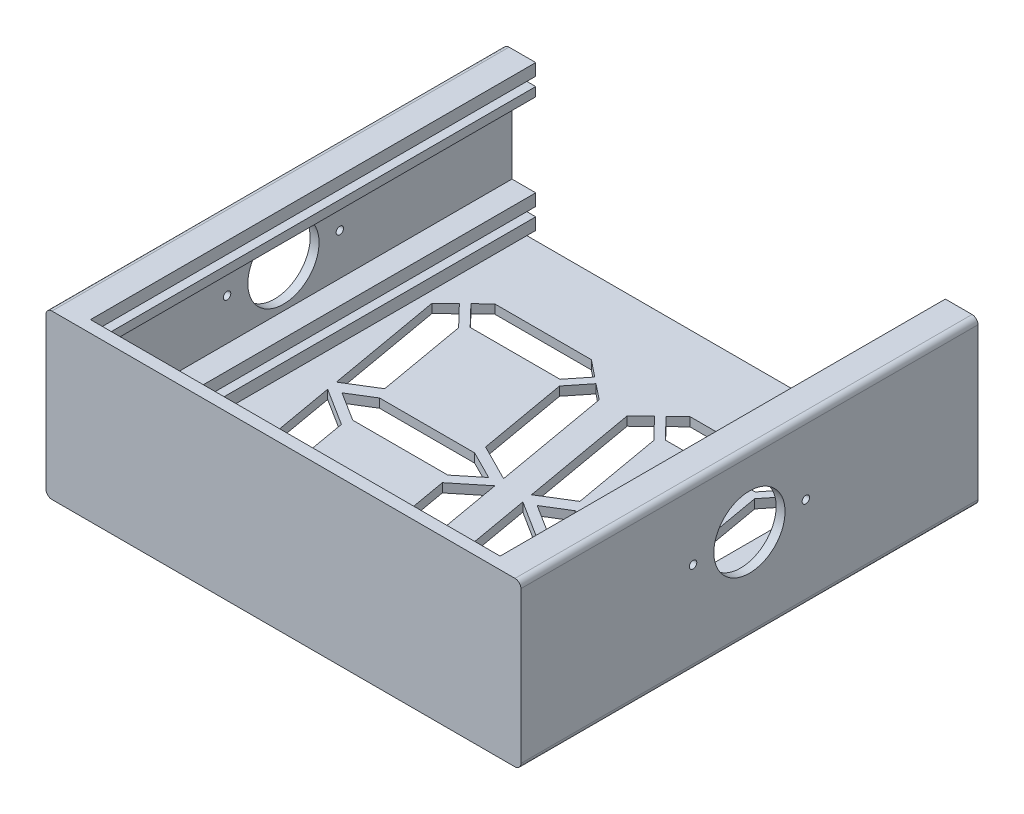
SolidWorks part; units mm, degrees
ref_plane "Alzado" through (0, 0, 0) normal (0, 0, 1) x (1, 0, 0)
ref_plane "Planta" through (0, 0, 0) normal (0, 1, 0) x (1, 0, 0)
ref_plane "Vista lateral" through (0, 0, 0) normal (1, 0, 0) x (0, 0, -1)
sketch "Sketch3" plane through (0, 0, 0) normal (0, 0, 1) x (1, 0, 0)
  line L0 (-80, 0) -> (80, 0)
  line L1 (-80, 0) -> (-80, 10)
  line L2 (-80, 10) -> (-69, 10)
  line L3 (-69, 10) -> (-69, 6)
  line L4 (-69, 6) -> (-77, 6)
  line L5 (-77, 6) -> (-77, 3)
  line L6 (-77, 3) -> (77, 3)
  line L8 (0, -2.3975) -> (0, 0) construction
  line L9 (77, 6) -> (77, 3)
  line L10 (69, 6) -> (77, 6)
  line L11 (69, 10) -> (69, 6)
  line L12 (80, 10) -> (69, 10)
  line L13 (80, 0) -> (80, 10)
  line L14 (0, 3) -> (0, 3.4015) construction
  point P4 (0, 0)
  dimension "D1" = 154
  dimension "D2" = 3
  dimension "D3" = 3
  dimension "D4" = 3
  dimension "D5" = 4
  dimension "D6" = 8
extrude "Boss-Extrude4" add sketch "Sketch3" along normal blind 154 contours L0 L13 L12 L11 L10 L9 L6 L5 L4 L3 L2 L1
sketch "Sketch11" plane through (-69, 0, 0) normal (1, 0, 0) x (0, 0, -1)
  line L1 (-154, 10) -> (-150, 10)
  line L2 (-154, 10) -> (-154, 3)
  line L3 (-154, 3) -> (-150, 3)
  line L4 (-150, 10) -> (-150, 3)
  point P5 (-150, 6.5)
  dimension "D1" = 4
extrude "Boss-Extrude5" add sketch "Sketch11" along normal through all and the other way up to next
sketch "Sketch13" plane through (0, 10, 0) normal (0, 1, 0) x (1, 0, 0)
  line L0 (80, 0) -> (77, 0)
  line L1 (77, 0) -> (77, -150)
  line L2 (77, -150) -> (-77, -150)
  line L3 (-77, -150) -> (-77, 0)
  line L4 (-77, 0) -> (-80, 0)
  line L5 (-80, 0) -> (-80, -154)
  line L6 (-80, -154) -> (80, -154)
  line L7 (80, -154) -> (80, 0)
  line L8 (77, -150) -> (77, 0) construction
  line L9 (80, 0) -> (69, 0) construction
  line L10 (-80, 0) -> (-69, 0) construction
  line L11 (69, -150) -> (-69, -150) construction
extrude "Boss-Extrude6" add sketch "Sketch13" along normal blind 45
sketch "Sketch15" plane through (0, 0, 150) normal (0, 0, -1) x (-1, 0, 0)
  line L0 (-69, 6) -> (-77, 6) construction
  line L1 (69, 6) -> (-69, 6)
  line L2 (69, 6) -> (69, 10)
  line L3 (69, 10) -> (-69, 10)
  line L4 (-69, 6) -> (-69, 10)
  line L5 (-77, 10) -> (-77, 55) construction
  line L7 (69, 10) -> (69, 6) construction
  line L8 (77, 13) -> (-77, 13)
  line L9 (77, 13) -> (77, 17)
  line L10 (77, 17) -> (-77, 17)
  line L11 (-77, 13) -> (-77, 17)
  line L18 (77, 55) -> (77, 10) construction
  dimension "D1" = 3
  dimension "D3" = 4
extrude "Boss-Extrude7" add sketch "Sketch15" along normal blind 8
sketch "Sketch16" plane through (-77, 0, 0) normal (1, 0, 0) x (0, 0, -1)
  line L0 (0, 10) -> (0, 6) construction
  line L1 (-142, 13) -> (-142, 17) construction
  line L2 (0, 55) -> (0, 10) construction
  line L3 (-142, 17) -> (-150, 17) construction
  line L5 (-150, 45) -> (0, 45)
  line L6 (-142, 17) -> (0, 17)
  line L7 (-142, 17) -> (-142, 13)
  line L8 (-142, 13) -> (0, 13)
  line L9 (0, 17) -> (0, 13)
  line L10 (-150, 48) -> (0, 48)
  line L11 (0, 48) -> (0, 45)
  line L12 (-150, 55) -> (-150, 51)
  line L14 (-150, 51) -> (0, 51)
  line L15 (0, 51) -> (0, 55)
  line L16 (0, 55) -> (-150, 55)
  line L17 (-150, 48) -> (-150, 45)
  line L19 (-150, 55) -> (0, 55) construction
  line L20 (-150, 55) -> (-150, 17) construction
  dimension "D1" = 4
  dimension "D2" = 3
  dimension "D3" = 3
  dimension "D4" = 3
extrude "Boss-Extrude8" add sketch "Sketch16" along normal blind 8
mirror "Mirror1" about plane through (0, 0, 0) normal (1, 0, 0) of "Boss-Extrude8"
sketch "Sketch19" plane through (80, 0, 0) normal (1, 0, 0) x (0, 0, -1)
  line L0 (-77, 55) -> (-77, 0) construction
  line L4 (-89, 31) -> (-65, 31) construction
  line L9 (-154, 55) -> (0, 55) construction
  line L10 (-154, 0) -> (0, 0) construction
  circle A0 centre (-77, 31) radius 12
  circle A1 centre (-58, 31) radius 1.25
  circle A2 centre (-96, 31) radius 1.25
  dimension "D1" = 24
  dimension "D2" = 24
  dimension "D3" = 2.5
  dimension "D4" = 7
extrude "Cut-Extrude2" cut sketch "Sketch19" against normal through all both and the other way through all
sketch "Sketch23" plane through (0, 0, 0) normal (0, -1, 0) x (1, 0, 0)
  line L0 (-121.4869, 35.4036) -> (-91.4869, 35.4036)
  line L1 (-91.4869, 35.4036) -> (-84.2782, 40.4629)
  line L2 (-84.2782, 40.4629) -> (-87.7457, 45.4036)
  line L3 (-87.7457, 45.4036) -> (-119.7237, 45.4036)
  line L4 (-119.7237, 45.4036) -> (-125.6072, 41.2743)
  line L5 (-125.6072, 41.2743) -> (-121.4869, 35.4036)
  line L6 (-86.9751, 47.7728) -> (-82.1493, 75.1414)
  line L7 (-82.1493, 75.1414) -> (-75.8378, 80.2286)
  line L8 (-75.8378, 80.2286) -> (-71.9488, 75.4036)
  line L9 (-86.9751, 47.7728) -> (-82.6478, 41.6072)
  line L10 (-82.6478, 41.6072) -> (-77.2386, 45.4036)
  line L11 (-77.2386, 45.4036) -> (-71.9488, 75.4036)
  line L12 (-75.5209, 82.0262) -> (-70.2605, 84.9783)
  line L13 (-70.2605, 84.9783) -> (-64.0537, 120.1793)
  line L14 (-64.0537, 120.1793) -> (-67.9896, 124.7385)
  line L15 (-67.9896, 124.7385) -> (-74.3762, 119.2249)
  line L16 (-74.3762, 119.2249) -> (-79.666, 89.2249)
  line L17 (-79.666, 89.2249) -> (-75.5209, 82.0262)
  line L18 (-82.6478, 41.6072) -> (-67.9896, 124.7385) construction
  line L19 (-111.1826, 124.7385) -> (-67.9896, 124.7385) construction
  line L20 (-107.2467, 120.1793) -> (-64.0537, 120.1793) construction
  line L21 (-117.5692, 119.2249) -> (-74.3762, 119.2249) construction
  line L22 (-118.7139, 82.0262) -> (-75.5209, 82.0262) construction
  line L23 (-113.4536, 84.9783) -> (-70.2605, 84.9783) construction
  line L24 (-122.859, 89.2249) -> (-79.666, 89.2249) construction
  line L25 (-115.1419, 75.4036) -> (-71.9488, 75.4036) construction
  line L26 (-125.3423, 75.1414) -> (-82.1493, 75.1414) construction
  line L27 (-120.4317, 45.4036) -> (-77.2386, 45.4036) construction
  line L28 (-130.1682, 47.7728) -> (-86.9751, 47.7728) construction
  line L29 (-125.8409, 41.6072) -> (-82.6478, 41.6072) construction
  line L30 (-105.3849, 120.2859) -> (-74.5419, 120.2859)
  line L31 (-74.5419, 120.2859) -> (-68.5852, 125.4284)
  line L32 (-68.5852, 125.4284) -> (-72.7787, 130.2859)
  line L33 (-72.7787, 130.2859) -> (-104.7566, 130.2859)
  line L34 (-104.7566, 130.2859) -> (-110.0631, 125.7049)
  line L35 (-110.0631, 125.7049) -> (-105.3849, 120.2859)
  line L36 (-119.0309, 80.2286) -> (-75.8378, 80.2286) construction
  line L38 (-130.1682, 47.7728) -> (-125.3423, 75.1414)
  line L39 (-125.3423, 75.1414) -> (-119.0309, 80.2286)
  line L40 (-119.0309, 80.2286) -> (-115.1419, 75.4036)
  line L41 (-130.1682, 47.7728) -> (-125.8409, 41.6072)
  line L42 (-125.8409, 41.6072) -> (-120.4317, 45.4036)
  line L43 (-120.4317, 45.4036) -> (-115.1419, 75.4036)
  line L44 (-118.7139, 82.0262) -> (-113.4536, 84.9783)
  line L45 (-113.4536, 84.9783) -> (-107.2467, 120.1793)
  line L46 (-107.2467, 120.1793) -> (-111.1826, 124.7385)
  line L47 (-111.1826, 124.7385) -> (-117.5692, 119.2249)
  line L48 (-117.5692, 119.2249) -> (-122.859, 89.2249)
  line L49 (-122.859, 89.2249) -> (-118.7139, 82.0262)
  line L50 (-125.8409, 41.6072) -> (-111.1826, 124.7385) construction
  line L55 (-87.7457, 45.4036) -> (-72.7787, 130.2859)
  line L56 (-121.4869, 35.4036) -> (-104.7566, 130.2859) construction
  dimension "D1" = 80
  dimension "D2" = 52.5368
  dimension "D4" = 30
  dimension "D5" = 30
sketch "Version 1" plane through (0, 0, 0) normal (0, -1, 0) x (1, 0, 0)
  line L0 (17.6283, 7.3254) -> (47.1035, 7.3254)
  line L1 (47.1035, 7.3254) -> (51.1504, 11.3591)
  line L2 (51.1504, 11.3591) -> (46.7616, 17.3254)
  line L3 (46.7616, 17.3254) -> (18.8884, 17.3254)
  line L4 (18.8884, 17.3254) -> (13.6565, 11.1604)
  line L5 (13.6565, 11.1604) -> (17.6283, 7.3254)
  line L6 (18.5241, 19.3035) -> (12.5336, 12.2447)
  line L7 (23.3426, 46.6307) -> (54.2531, 46.6307) construction
  line L8 (14.1831, 52.2722) -> (23.3426, 46.6307)
  line L9 (23.3426, 46.6307) -> (18.5241, 19.3035)
  line L10 (12.5336, 12.2447) -> (7.912, 16.7071)
  line L11 (7.912, 16.7071) -> (14.1831, 52.2722)
  line L12 (49.2177, 18.0734) -> (52.8849, 13.088)
  line L13 (52.8849, 13.088) -> (59.6887, 19.8696)
  line L14 (59.6887, 19.8696) -> (65.4021, 52.2722)
  line L15 (14.1831, 52.2722) -> (65.4021, 52.2722) construction
  line L16 (65.4021, 52.2722) -> (54.2531, 46.6307)
  line L17 (54.2531, 46.6307) -> (49.2177, 18.0734)
  line L18 (18.2172, 54.0616) -> (24.941, 49.9203)
  line L19 (24.941, 49.9203) -> (54.0632, 49.9203)
  line L20 (54.0632, 49.9203) -> (62.2475, 54.0616)
  line L21 (62.2475, 54.0616) -> (55.9407, 59.9203)
  line L22 (55.9407, 59.9203) -> (26.7795, 59.9203)
  line L23 (26.7795, 59.9203) -> (18.2172, 54.0616)
  line L24 (14.7578, 55.5316) -> (20.5772, 88.5347)
  line L25 (20.5772, 88.5347) -> (25.4267, 92.8942)
  line L26 (25.4267, 92.8942) -> (30.5042, 87.246)
  line L27 (30.5042, 87.246) -> (26.3053, 63.4328)
  line L28 (26.3053, 63.4328) -> (14.7578, 55.5316)
  line L29 (57.2158, 63.4328) -> (65.9409, 55.3277)
  line L30 (65.9409, 55.3277) -> (71.7962, 88.5347)
  line L31 (71.7962, 88.5347) -> (67.1519, 93.2534)
  line L32 (67.1519, 93.2534) -> (61.4147, 87.246)
  line L33 (61.4147, 87.246) -> (57.2158, 63.4328)
  line L34 (26.3053, 63.4328) -> (57.2158, 63.4328) construction
  line L35 (18.2172, 54.0616) -> (62.2475, 54.0616) construction
  line L36 (26.9247, 94.2408) -> (31.2033, 89.4813)
  line L37 (31.2033, 89.4813) -> (60.7361, 89.4813)
  line L38 (60.7361, 89.4813) -> (65.724, 94.7042)
  line L39 (65.724, 94.7042) -> (61.0223, 99.4813)
  line L40 (61.0223, 99.4813) -> (32.7542, 99.4813)
  line L41 (32.7542, 99.4813) -> (26.9247, 94.2408)
  line L42 (20.5772, 88.5347) -> (71.7962, 88.5347) construction
  line L43 (30.5042, 87.246) -> (61.4147, 87.246) construction
  dimension "D1" = 80
  dimension "D2" = 37.4939
  dimension "D3" = 40.0275
  dimension "D4" = 44.0303
  dimension "D5" = 27.3271
sketch "Sketch27" plane through (0, 0, 0) normal (0, -1, 0) x (1, 0, 0)
  line L0 (-80, 0) -> (80, 0) construction
  line L1 (2.5, 154) -> (2.5, 0) construction
  line L2 (-68.253, 35.7252) -> (-80, 35.7252) construction
  line L3 (-2.5, 154) -> (-2.5, 0) construction
  line L48 (-80, 154) -> (-80, 0) construction
  line L49 (0, 77) -> (-80, 77) construction
  line L51 (0, 0) -> (0, 154) construction
  line L52 (-80, 154) -> (80, 154) construction
  line B0 (-57.4785, 25.3217) -> (-24.9357, 25.3217)
  line B1 (-24.9357, 25.3217) -> (-19.3054, 29.8193)
  line B2 (-19.3054, 29.8193) -> (-24.4996, 36.3217)
  line B3 (-24.4996, 36.3217) -> (-54.7714, 36.3217)
  line B4 (-54.7714, 36.3217) -> (-61.5742, 29.2763)
  line B5 (-61.5742, 29.2763) -> (-57.4785, 25.3217)
  line B6 (-56.6171, 38.3693) -> (-63.5525, 31.1865)
  line B7 (-51.2841, 68.6138) -> (-17.2826, 68.6138) construction
  line B8 (-61.3596, 74.8195) -> (-51.2841, 68.6138)
  line B9 (-51.2841, 68.6138) -> (-56.6171, 38.3693)
  line B10 (-63.5525, 31.1865) -> (-68.253, 35.7252)
  line B11 (-68.253, 35.7252) -> (-61.3596, 74.8195)
  line B12 (-22.6155, 38.3693) -> (-17.1568, 31.5357)
  line B13 (-17.1568, 31.5357) -> (-11.9121, 35.7252)
  line B14 (-11.9121, 35.7252) -> (-5.0187, 74.8195)
  line B15 (-61.3596, 74.8195) -> (-5.0187, 74.8195) construction
  line B16 (-5.0187, 74.8195) -> (-17.2826, 68.6138)
  line B17 (-17.2826, 68.6138) -> (-22.6155, 38.3693)
  line B18 (-57.2666, 77) -> (-49.4345, 72.1761)
  line B19 (-49.4345, 72.1761) -> (-17.4001, 72.1761)
  line B20 (-17.4001, 72.1761) -> (-7.8667, 77)
  line B21 (-7.8667, 77) -> (-15.4605, 83.1761)
  line B22 (-15.4605, 83.1761) -> (-47.4949, 83.1761)
  line B23 (-47.4949, 83.1761) -> (-57.2666, 77)
  line B24 (-60.7343, 78.3659) -> (-53.8409, 117.4601)
  line B25 (-53.8409, 117.4601) -> (-47.5815, 123.0871)
  line B26 (-47.5815, 123.0871) -> (-42.6469, 117.5979)
  line B27 (-42.6469, 117.5979) -> (-48.1637, 86.3109)
  line B28 (-48.1637, 86.3109) -> (-60.7343, 78.3659)
  line B29 (-14.1621, 86.3109) -> (-4.3934, 78.3659)
  line B30 (-4.3934, 78.3659) -> (2.5, 117.4601)
  line B31 (2.5, 117.4601) -> (-2.2352, 123.0388)
  line B32 (-2.2352, 123.0388) -> (-8.6454, 117.5979)
  line B33 (-8.6454, 117.5979) -> (-14.1621, 86.3109)
  line B34 (-48.1637, 86.3109) -> (-14.1621, 86.3109) construction
  line B35 (-57.2666, 77) -> (-7.8667, 77) construction
  line B36 (-45.5364, 124.9256) -> (-41.4445, 120.3738)
  line B37 (-41.4445, 120.3738) -> (-9.6247, 120.3738)
  line B38 (-9.6247, 120.3738) -> (-4.0148, 125.1354)
  line B39 (-4.0148, 125.1354) -> (-9.3098, 131.3738)
  line B40 (-9.3098, 131.3738) -> (-38.3635, 131.3738)
  line B41 (-38.3635, 131.3738) -> (-45.5364, 124.9256)
  line B42 (-53.8409, 117.4601) -> (2.5, 117.4601) construction
  line B43 (-42.6469, 117.5979) -> (-8.6454, 117.5979) construction
  line B44 (-56.6171, 38.3693) -> (-22.6155, 38.3693) construction
  line B45 (-68.253, 35.7252) -> (-11.9121, 35.7252) construction
  line B46 (-49.4345, 72.1761) -> (-47.4949, 83.1761) construction
  line B47 (-17.4001, 72.1761) -> (-15.4605, 83.1761) construction
  line B48 (-63.5525, 31.1865) -> (-61.5742, 29.2763) construction
  line B49 (-19.3054, 29.8193) -> (-17.1568, 31.5357) construction
  line B50 (-47.5815, 123.0871) -> (-45.5364, 124.9256) construction
  line B51 (-4.0148, 125.1354) -> (-2.2352, 123.0388) construction
  line B52 (8.2745, 25.3217) -> (40.8173, 25.3217)
  line B53 (40.8173, 25.3217) -> (46.4476, 29.8193)
  line B54 (46.4476, 29.8193) -> (41.2534, 36.3217)
  line B55 (41.2534, 36.3217) -> (10.9816, 36.3217)
  line B56 (10.9816, 36.3217) -> (4.1788, 29.2763)
  line B57 (4.1788, 29.2763) -> (8.2745, 25.3217)
  line B58 (9.1359, 38.3693) -> (2.2005, 31.1865)
  line B59 (4.3934, 74.8195) -> (14.4688, 68.6138)
  line B60 (14.4688, 68.6138) -> (9.1359, 38.3693)
  line B61 (2.2005, 31.1865) -> (-2.5, 35.7252)
  line B62 (-2.5, 35.7252) -> (4.3934, 74.8195)
  line B63 (43.1374, 38.3693) -> (48.5962, 31.5357)
  line B64 (48.5962, 31.5357) -> (53.8409, 35.7252)
  line B65 (53.8409, 35.7252) -> (60.7343, 74.8195)
  line B66 (60.7343, 74.8195) -> (48.4704, 68.6138)
  line B67 (48.4704, 68.6138) -> (43.1374, 38.3693)
  line B68 (8.4863, 77) -> (16.3185, 72.1761)
  line B69 (16.3185, 72.1761) -> (48.3529, 72.1761)
  line B70 (48.3529, 72.1761) -> (57.8862, 77)
  line B71 (57.8862, 77) -> (50.2925, 83.1761)
  line B72 (50.2925, 83.1761) -> (18.2581, 83.1761)
  line B73 (18.2581, 83.1761) -> (8.4863, 77)
  line B74 (5.0187, 78.3659) -> (11.9121, 117.4601)
  line B75 (11.9121, 117.4601) -> (18.1715, 123.0871)
  line B76 (18.1715, 123.0871) -> (23.1061, 117.5979)
  line B77 (23.1061, 117.5979) -> (17.5893, 86.3109)
  line B78 (17.5893, 86.3109) -> (5.0187, 78.3659)
  line B79 (51.5908, 86.3109) -> (61.3596, 78.3659)
  line B80 (61.3596, 78.3659) -> (68.253, 117.4601)
  line B81 (68.253, 117.4601) -> (63.5178, 123.0388)
  line B82 (63.5178, 123.0388) -> (57.1076, 117.5979)
  line B83 (57.1076, 117.5979) -> (51.5908, 86.3109)
  line B84 (8.4863, 77) -> (57.8862, 77) construction
  line B85 (20.2166, 124.9256) -> (24.3085, 120.3738)
  line B86 (24.3085, 120.3738) -> (56.1283, 120.3738)
  line B87 (56.1283, 120.3738) -> (61.7382, 125.1354)
  line B88 (61.7382, 125.1354) -> (56.4432, 131.3738)
  line B89 (56.4432, 131.3738) -> (27.3895, 131.3738)
  line B90 (27.3895, 131.3738) -> (20.2166, 124.9256)
  dimension "D1" = 2.5
  dimension "D2" = 2.5
sketch_block_instance "Block1-1"
sketch_block "Block1" parameters "D1"=80, "D2"=44.909, "D3"=1.6361, "D4"=28.8815, "D5"=29.5328, "D6"=28.4427, "D7"=29.1222, "D8"=27.4951, "D9"=29.5843, "D10"=0.6294, "D11"=3
sketch_block_instance "Block1-2"
extrude "Cut-Extrude3" cut sketch "Sketch27" against normal up to next
sketch "Sketch34" plane through (77, 0, 0) normal (-1, 0, 0) x (0, 0, 1)
  line L0 (0, 27) -> (0, 35)
  line L2 (0, 35) -> (15, 35)
  line L3 (15, 35) -> (15, 27)
  line L4 (15, 27) -> (0, 27)
  line L5 (0, 45) -> (0, 17) construction
  point P6 (0, 31)
  point P11 (0, 31)
  dimension "D1" = 15
  dimension "D2" = 8
fillet "Fillet3" radius 2 4 edges at (-80, 0, 77) (80, 0, 77) (-80, 55, 77) (80, 55, 77)
equation "\"D3\"= 2 * \"Center to mid\""
